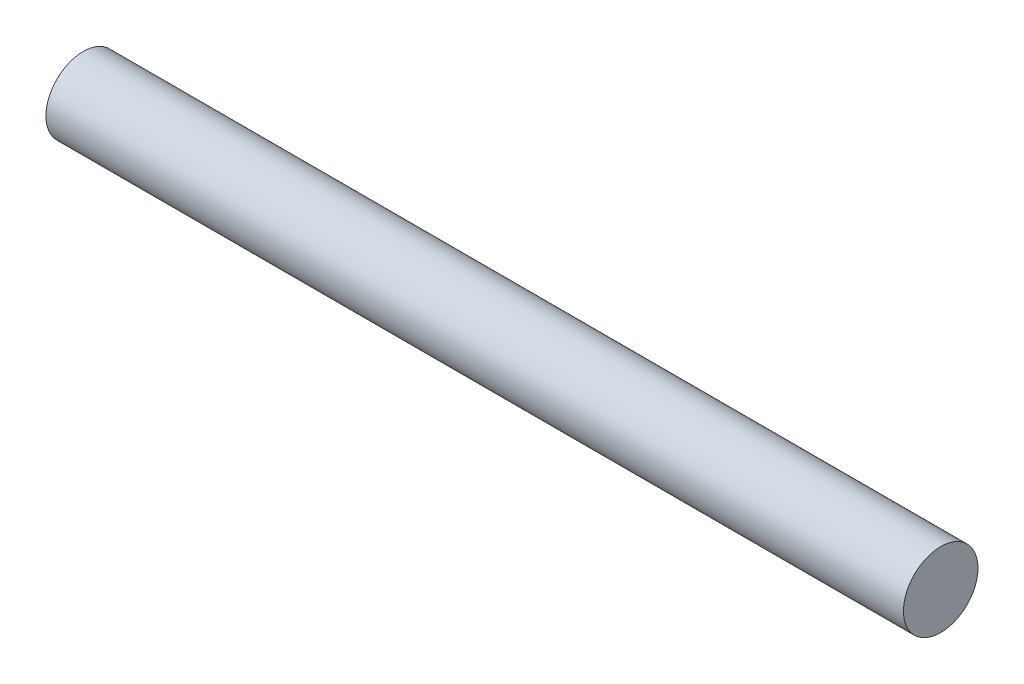
SolidWorks part; units mm, degrees
ref_plane "Front Plane" through (0, 0, 0) normal (0, 0, 1) x (1, 0, 0)
ref_plane "Top Plane" through (0, 0, 0) normal (0, 1, 0) x (1, 0, 0)
ref_plane "Right Plane" through (0, 0, 0) normal (1, 0, 0) x (0, 0, -1)
sketch "Sketch1" plane through (0, 0, 0) normal (1, 0, 0) x (0, 0, -1)
  circle A0 centre (0, 0) radius 1
  dimension "D1" = 2
extrude "Boss-Extrude1" add sketch "Sketch1" along normal blind 23
ref_plane "Plane1" through (11.5, 0, 0) normal (1, 0, 0) x (0, 0, -1)
